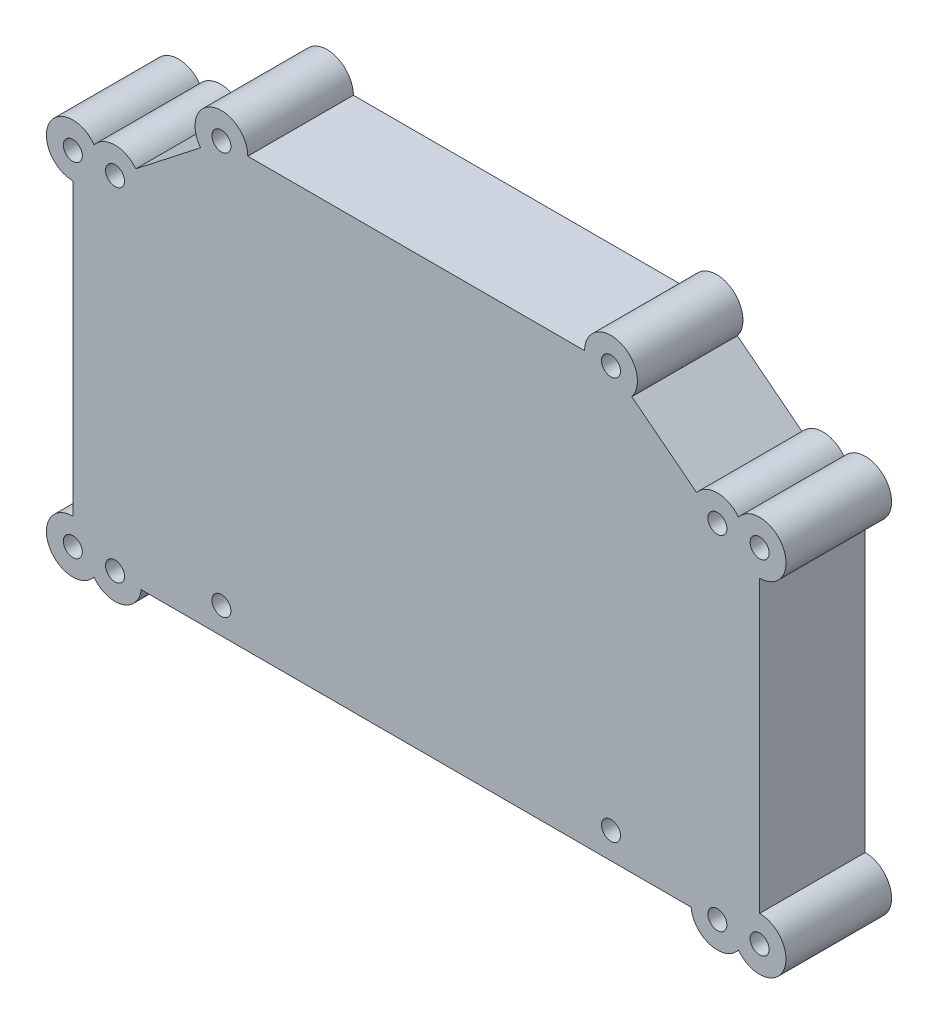
SolidWorks part; units mm, degrees
ref_plane "Front Plane" through (0, 0, 0) normal (0, 0, 1) x (1, 0, 0)
ref_plane "Top Plane" through (0, 0, 0) normal (0, 1, 0) x (1, 0, 0)
ref_plane "Right Plane" through (0, 0, 0) normal (1, 0, 0) x (0, 0, -1)
sketch "Sketch2" plane through (0, 0, 0) normal (0, 0, 1) x (1, 0, 0)
  line L0 (55, 0) -> (-55, 0) construction
  line L1 (86.3487, -50.5747) -> (-86.3487, -50.5747) construction
  line L2 (86.3487, -50.5747) -> (86.3487, 50.5747) construction
  line L3 (86.3487, 50.5747) -> (-86.3487, 50.5747) construction
  line L4 (-86.3487, -50.5747) -> (-86.3487, 50.5747) construction
  line L5 (86.3487, -50.5747) -> (-86.3487, 50.5747) construction
  line L6 (86.3487, 50.5747) -> (-86.3487, -50.5747) construction
  line L7 (0, -55) -> (0, 55) construction
  line L8 (-76.4163, 22.4861) -> (-48.7512, 22.4861) construction
  line L9 (-78.4765, -42.5139) -> (-51.5471, -42.5139) construction
  line L10 (51.414, 22.35) -> (70.6588, 22.35) construction
  line L11 (51.414, -42.65) -> (75.8428, -42.65) construction
  line L12 (-65.0488, 17.4861) -> (-65.05, -37.5139)
  line L13 (-36.9, -43.1) -> (36.9, -43.1)
  line L14 (-36.9, -43.1) -> (-52.0845, -43.1)
  line L15 (36.9, -43.1) -> (52.0703, -43.1)
  line L16 (65.05, 17.35) -> (65.05, -37.65)
  line L18 (-53.1106, 25.4292) -> (-40.8394, 35.0208)
  line L19 (-31.9, 38.1) -> (31.9, 38.1)
  line L20 (-80.0488, 25.4861) -> (-41.05, 25.4861) construction
  line L21 (40.8394, 35.0208) -> (53.1106, 25.4292)
  line L22 (-80.0488, 25.4861) -> (-80.0488, -45.5139) construction
  line L23 (-80.0488, -45.5139) -> (-41.05, -45.5139) construction
  line L24 (-41.05, 25.4861) -> (-41.05, -45.5139) construction
  line L25 (41, 25.35) -> (80.3, 25.35) construction
  line L26 (41, 25.35) -> (41, -45.65) construction
  line L27 (41, -45.65) -> (80.3, -45.65) construction
  line L28 (80.3, 25.35) -> (80.3, -45.65) construction
  circle A4 centre (-36.9, -38.1) radius 1.8
  circle A5 centre (-36.9, 38.1) radius 1.8
  circle A6 centre (36.9, -38.1) radius 1.8
  circle A7 centre (36.9, 38.1) radius 1.8
  circle A8 centre (-65.0488, 22.4861) radius 1.8
  circle A9 centre (-57.05, 22.35) radius 1.8
  circle A10 centre (-65.05, -42.5139) radius 1.8
  circle A12 centre (-57.05, -42.5139) radius 1.8
  circle A13 centre (57.05, 22.35) radius 1.8
  circle A14 centre (65.05, 22.35) radius 1.8
  circle A15 centre (57.05, -42.65) radius 1.8
  circle A16 centre (65.05, -42.65) radius 1.8
  arc A17 (-60.9984, 25.4176) -> (-65.0488, 17.4861) centre (-65.0488, 22.4861) ccw
  arc A18 (-53.1106, 25.4292) -> (-60.9984, 25.4176) centre (-57.05, 22.35) ccw
  arc A19 (-31.9, 38.1) -> (-40.8394, 35.0208) centre (-36.9, 38.1) ccw
  arc A20 (40.8394, 35.0208) -> (31.9, 38.1) centre (36.9, 38.1) ccw
  arc A21 (61.05, 25.35) -> (53.1106, 25.4292) centre (57.05, 22.35) ccw
  arc A22 (65.05, 17.35) -> (61.05, 25.35) centre (65.05, 22.35) ccw
  arc A23 (52.05, -42.65) -> (61.05, -45.65) centre (57.05, -42.65) ccw
  arc A24 (61.05, -45.65) -> (65.05, -37.65) centre (65.05, -42.65) ccw
  circle A25 centre (-36.9, -38.1) radius 5 construction
  arc A26 (-61.05, -45.5139) -> (-52.0845, -43.1) centre (-57.05, -42.5139) ccw
  arc A27 (-65.05, -37.5139) -> (-61.05, -45.5139) centre (-65.05, -42.5139) ccw
  circle A28 centre (36.9, -38.1) radius 5 construction
  point P0 (0, 0)
  dimension "D1" = 65
  dimension "D2" = 38.1
  dimension "D3" = 8
  dimension "D8" = 28.15
  dimension "D9" = 20.15
  dimension "D10" = 8
  dimension "D12" = 65
  dimension "D14" = 3
  dimension "D4" = 73.8
  dimension "D5" = 15.75
  dimension "D6" = 20.15
  dimension "D7" = 73.8
  dimension "D11" = 15.75
  dimension "D13" = 8
  dimension "D15" = 3
  dimension "D16" = 15
  dimension "D17" = 3
  dimension "D18" = 3
  dimension "D19" = 15.25
  dimension "D20" = 16.05
  dimension "D21" = 16
extrude "Boss-Extrude1" add sketch "Sketch2" along normal blind 20
